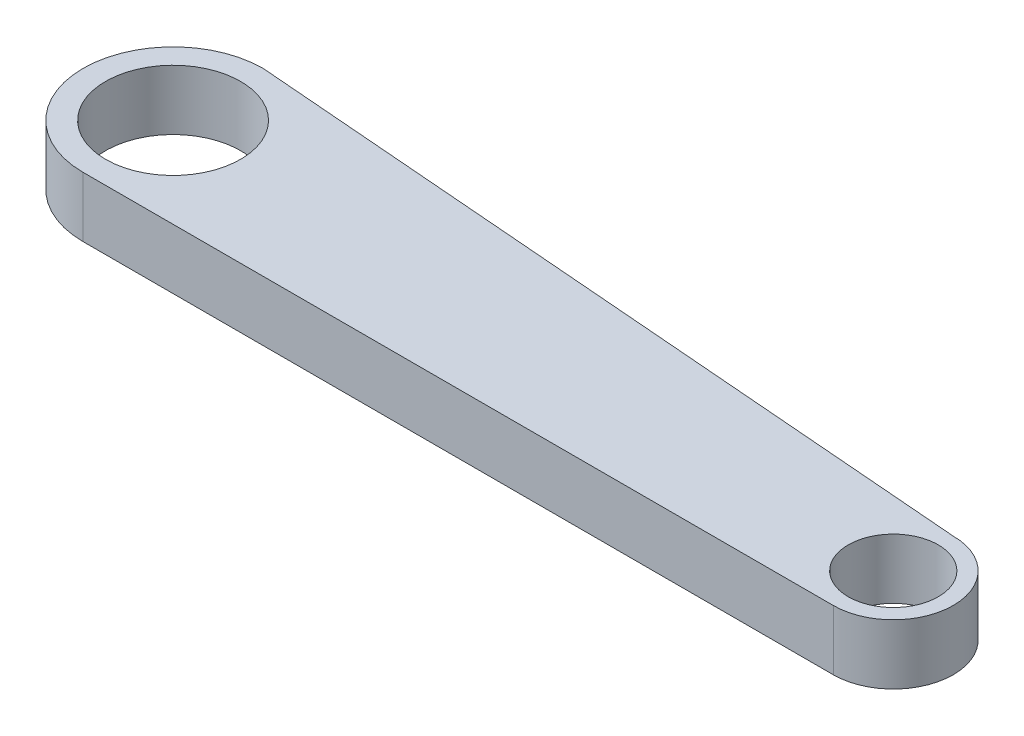
SolidWorks part; units mm, degrees
ref_plane "Front Plane" through (0, 0, 0) normal (0, 0, 1) x (1, 0, 0)
ref_plane "Top Plane" through (0, 0, 0) normal (0, 1, 0) x (1, 0, 0)
ref_plane "Right Plane" through (0, 0, 0) normal (1, 0, 0) x (0, 0, -1)
sketch "Sketch1" plane through (0, 0, 0) normal (0, 1, 0) x (1, 0, 0)
  line L0 (0, -96) -> (800, -96)
  line L1 (800, -96) -> (800, 32)
  line L2 (800, 32) -> (0, 96)
  circle A0 centre (0, 0) radius 96
  circle A1 centre (0, 0) radius 72
  circle A2 centre (800, -32) radius 64
  circle A3 centre (800, -32) radius 48
  dimension "D1" = 144
  dimension "D2" = 192
  dimension "D5" = 96
  dimension "D3" = 800
  dimension "D4" = 128
extrude "Boss-Extrude2" add sketch "Sketch1" along normal blind 64 contours A0 L2 A1 | A2 L2 A0 L0 | A3 L1 A2 | A3 L1 A2
